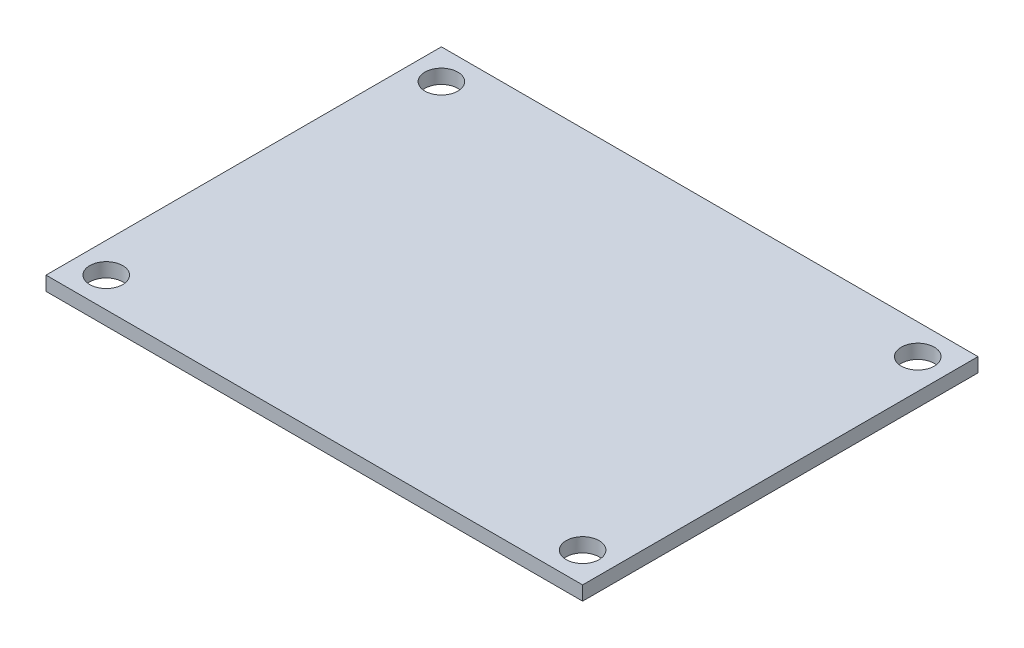
SolidWorks part; units mm, degrees
ref_plane "Front Plane" through (0, 0, 0) normal (0, 0, 1) x (1, 0, 0)
ref_plane "Top Plane" through (0, 0, 0) normal (0, 1, 0) x (1, 0, 0)
ref_plane "Right Plane" through (0, 0, 0) normal (1, 0, 0) x (0, 0, -1)
sketch "Sketch1" plane through (0, 0, 0) normal (0, 1, 0) x (1, 0, 0)
  line L1 (-28.5, -21) -> (28.5, -21)
  line L2 (-28.5, -21) -> (-28.5, 21)
  line L3 (-28.5, 21) -> (28.5, 21)
  line L4 (28.5, -21) -> (28.5, 21)
  line L5 (-28.5, -21) -> (28.5, 21) construction
  line L6 (-28.5, 21) -> (28.5, -21) construction
  point P0 (0, 0)
  dimension "D1" = 57
  dimension "D2" = 42
extrude "Boss-Extrude1" add sketch "Sketch1" along normal blind 1.5
sketch "Sketch2" plane through (0, 1.5, 0) normal (0, 1, 0) x (1, 0, 0)
  line L1 (25.3, -17.8) -> (-25.3, -17.8) construction
  line L2 (25.3, -17.8) -> (25.3, 17.8) construction
  line L3 (25.3, 17.8) -> (-25.3, 17.8) construction
  line L4 (-25.3, -17.8) -> (-25.3, 17.8) construction
  line L5 (25.3, -17.8) -> (-25.3, 17.8) construction
  line L6 (25.3, 17.8) -> (-25.3, -17.8) construction
  circle A0 centre (-25.3, 17.8) radius 1.75
  circle A1 centre (-25.3, -17.8) radius 1.75
  circle A2 centre (25.3, -17.8) radius 1.75
  circle A3 centre (25.3, 17.8) radius 1.75
  point P0 (0, 0)
  dimension "D3" = 3.5
  dimension "D1" = 35.6
  dimension "D2" = 50.6
extrude "Cut-Extrude1" cut sketch "Sketch2" against normal blind 10
